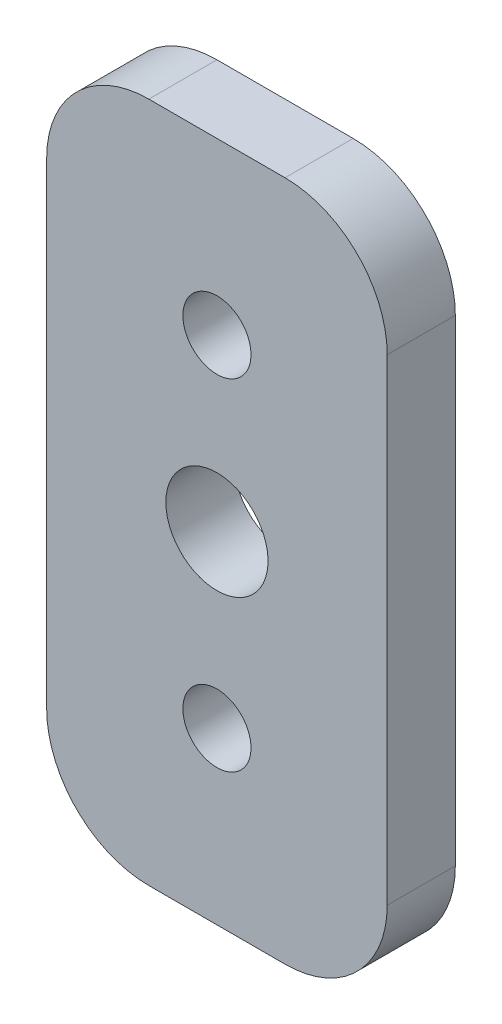
SolidWorks part; units mm, degrees
ref_plane "Plan de face" through (0, 0, 0) normal (0, 0, 1) x (1, 0, 0)
ref_plane "Plan de dessus" through (0, 0, 0) normal (0, 1, 0) x (1, 0, 0)
ref_plane "Plan de droite" through (0, 0, 0) normal (1, 0, 0) x (0, 0, -1)
sketch "Esquisse3" plane through (0, 0, 0) normal (0, 0, 1) x (1, 0, 0)
  line L1 (-25, -50) -> (25, -50)
  line L2 (-25, -50) -> (-25, 50)
  line L3 (-25, 50) -> (25, 50)
  line L4 (25, -50) -> (25, 50)
  line L5 (-5, -30) -> (5, -30) construction
  line L6 (-5, -30) -> (-5, 30) construction
  line L7 (-5, 30) -> (5, 30) construction
  line L8 (5, -30) -> (5, 30) construction
  point P4 (0, 0)
  dimension "D1" = 100
  dimension "D2" = 50
  dimension "D3" = 25
  dimension "D4" = 50
  dimension "D5" = 20
  dimension "D6" = 20
  dimension "D7" = 20
  dimension "D8" = 20
extrude "Boss.-Extru.2" add sketch "Esquisse3" along normal blind 10
fillet "Congé1" radius 15 4 edges at (-25, -50, 5) (-25, 50, 5) (25, 50, 5) (25, -50, 5)
sketch "Esquisse4" plane through (0, 0, 0) normal (0, 0, -1) x (-1, 0, 0)
  line L0 (0, -25) -> (0, 25) construction
  circle A0 centre (0, -25) radius 5
  circle A1 centre (0, 25) radius 5
  circle A2 centre (0, 0) radius 7.5
  dimension "D3" = 10
  dimension "D4" = 10
  dimension "D5" = 15
  dimension "D1" = 25
  dimension "D2" = 50
extrude "Enlèv. mat.-Extru.1" cut sketch "Esquisse4" against normal blind 10
